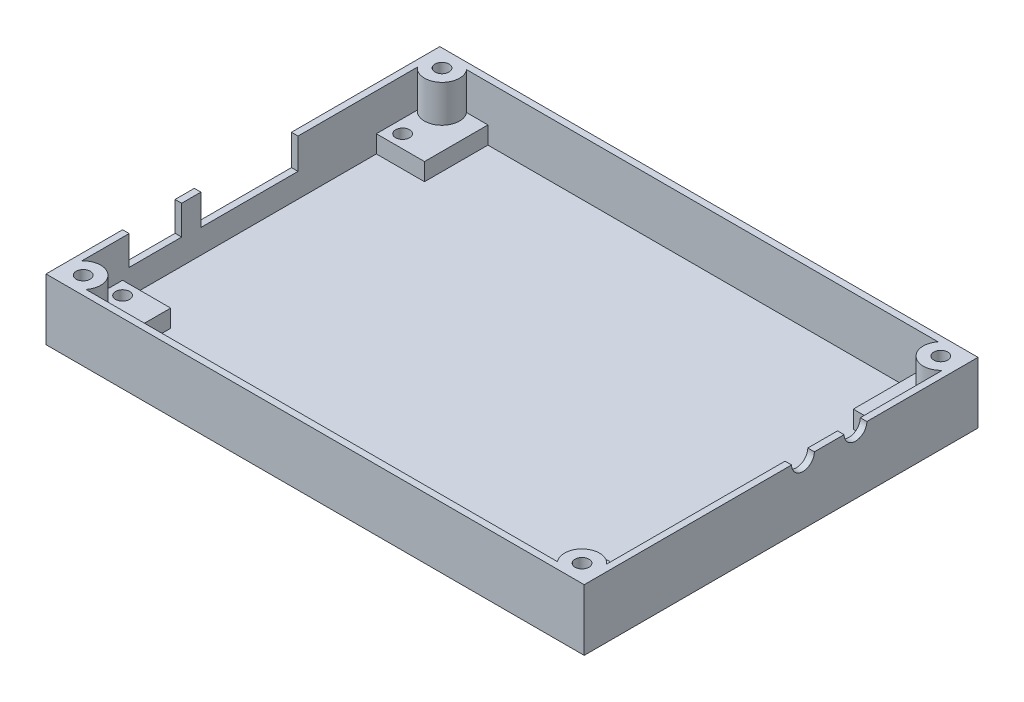
SolidWorks part; units mm, degrees
material "7079 Сплав"
ref_plane "Спереди" through (0, 0, 0) normal (0, 0, 1) x (1, 0, 0)
ref_plane "Сверху" through (0, 0, 0) normal (0, 1, 0) x (1, 0, 0)
ref_plane "Справа" through (0, 0, 0) normal (1, 0, 0) x (0, 0, -1)
sketch "Эскиз1" plane through (0, 0, 0) normal (0, 1, 0) x (1, 0, 0)
  line L1 (-61.5, 45) -> (61.5, 45)
  line L2 (-61.5, 45) -> (-61.5, -45)
  line L3 (-61.5, -45) -> (61.5, -45)
  line L4 (61.5, 45) -> (61.5, -45)
extrude "Бобышка-Вытянуть1" add sketch "Эскиз1" along normal blind 14
sketch "Эскиз2" plane through (0, 14, 0) normal (0, 1, 0) x (1, 0, 0)
  line L1 (60, -43.5) -> (-60, -43.5)
  line L2 (60, -43.5) -> (60, 43.5)
  line L3 (60, 43.5) -> (-60, 43.5)
  line L4 (-60, -43.5) -> (-60, 43.5)
  line L5 (60, -43.5) -> (-60, 43.5) construction
  line L6 (60, 43.5) -> (-60, -43.5) construction
  point P0 (0, 0)
extrude "Вырез-Вытянуть1" cut sketch "Эскиз2" against normal offset from surface (12.5 mm away) 1.5 up to face at (0, 0, 0)
sketch "Эскиз3" plane through (0, 1.5, 0) normal (0, 1, 0) x (1, 0, 0)
  line L1 (-61.5, 45) -> (-49, 45)
  line L2 (-61.5, 45) -> (-61.5, 29)
  line L3 (-61.5, 29) -> (-49, 29)
  line L4 (-49, 45) -> (-49, 29)
  line L5 (61.5, 45) -> (49, 45)
  line L6 (61.5, 45) -> (61.5, 29)
  line L7 (61.5, 29) -> (49, 29)
  line L8 (49, 45) -> (49, 29)
  line L9 (61.5, -45) -> (49, -45)
  line L10 (61.5, -45) -> (61.5, -29)
  line L11 (61.5, -29) -> (49, -29)
  line L12 (49, -45) -> (49, -29)
  line L13 (-61.5, -45) -> (-49, -45)
  line L14 (-61.5, -45) -> (-61.5, -29)
  line L15 (-61.5, -29) -> (-49, -29)
  line L16 (-49, -45) -> (-49, -29)
extrude "Бобышка-Вытянуть2" add sketch "Эскиз3" along normal blind 4
sketch "Эскиз4" plane through (0, 5.5, 0) normal (0, 1, 0) x (1, 0, 0)
  circle A0 centre (-57, 41) radius 4
  circle A1 centre (57, 41) radius 4
  circle A2 centre (57, -41) radius 4
  circle A3 centre (-57, -41) radius 4
extrude "Бобышка-Вытянуть3" add sketch "Эскиз4" along normal up to surface (8.5 mm away) up to face at (0, 14, 0)
sketch "Эскиз5" plane through (0, 0, 0) normal (0, 1, 0) x (1, 0, 0)
  circle A0 centre (-57, 41) radius 3
  circle A1 centre (57, 41) radius 3
  circle A2 centre (57, -41) radius 3
  circle A3 centre (-57, -41) radius 3
extrude "Вырез-Вытянуть2" cut sketch "Эскиз5" along normal blind 3
sketch "Эскиз6" plane through (0, 14, 0) normal (0, 1, 0) x (1, 0, 0)
  circle A0 centre (-57, 41) radius 1.6
  circle A1 centre (57, 41) radius 1.6
  circle A2 centre (57, -41) radius 1.6
  circle A3 centre (-57, -41) radius 1.6
extrude "Вырез-Вытянуть3" cut sketch "Эскиз6" against normal up to surface (11 mm away) up to face at (-57, 3, 44)
sketch "Эскиз7" plane through (61.5, 0, 0) normal (1, 0, 0) x (0, 0, -1)
  circle A0 centre (17, 14) radius 2.6
  circle A1 centre (5, 14) radius 2.6
extrude "Вырез-Вытянуть4" cut sketch "Эскиз7" against normal up to surface (1.5 mm away) up to face at (60, 6.625, 0)
sketch "Эскиз8" plane through (-61.5, 0, 0) normal (-1, 0, 0) x (0, 0, 1)
  line L1 (-11.1, 7) -> (11.1, 7)
  line L2 (-11.1, 7) -> (-11.1, 14)
  line L3 (-11.1, 14) -> (11.1, 14)
  line L4 (11.1, 7) -> (11.1, 14)
  line L5 (27.5, 7.3) -> (15.5, 7.3)
  line L6 (27.5, 7.3) -> (27.5, 14)
  line L7 (27.5, 14) -> (15.5, 14)
  line L8 (15.5, 7.3) -> (15.5, 14)
extrude "Вырез-Вытянуть5" cut sketch "Эскиз8" against normal up to surface (1.5 mm away) up to face at (-60, 6.625, 0)
sketch "Эскиз9" plane through (0, 5.5, 0) normal (0, 1, 0) x (-1, 0, 0)
  circle A0 centre (57, 32) radius 1.6
  circle A1 centre (57, -32) radius 1.6
  circle A2 centre (-57, -32) radius 1.6
  circle A3 centre (-57, 32) radius 1.6
extrude "Вырез-Вытянуть6" cut sketch "Эскиз9" against normal blind 4
